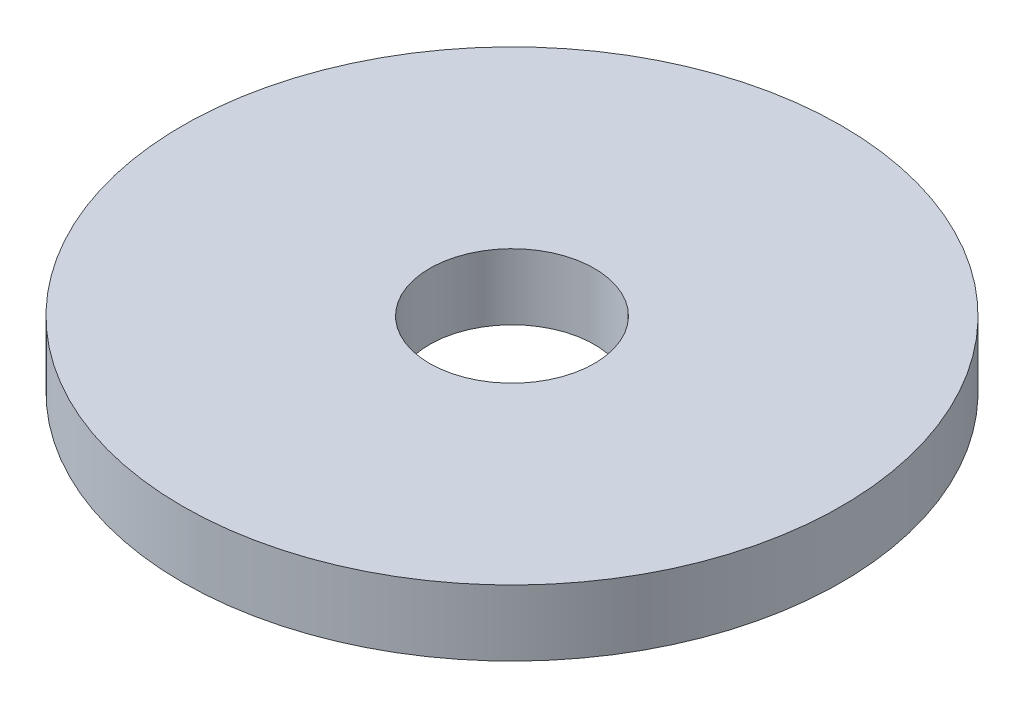
SolidWorks part; units mm, degrees
ref_plane "Front Plane" through (0, 0, 0) normal (0, 0, 1) x (1, 0, 0)
ref_plane "Top Plane" through (0, 0, 0) normal (0, 1, 0) x (1, 0, 0)
ref_plane "Right Plane" through (0, 0, 0) normal (1, 0, 0) x (0, 0, -1)
sketch "Sketch2" plane through (0, 0, 0) normal (0, 1, 0) x (1, 0, 0)
  circle A0 centre (0, 0) radius 2.5
  circle A1 centre (0, 0) radius 10
  dimension "D1" = 5
  dimension "D2" = 20
extrude "Boss-Extrude1" add sketch "Sketch2" along normal blind 2
